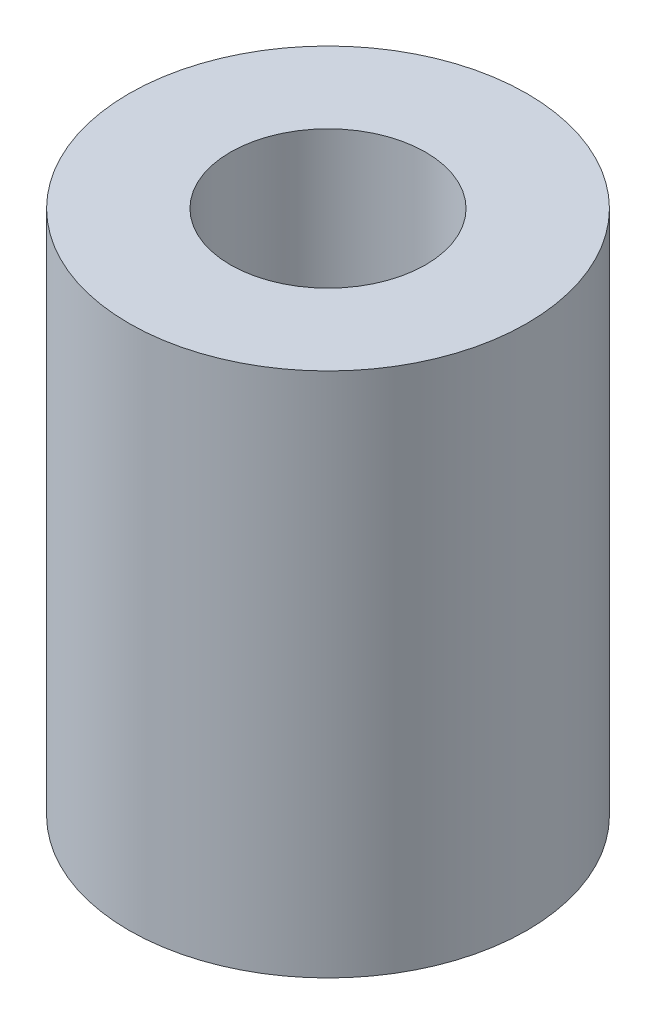
SolidWorks part; units mm, degrees
ref_plane "Front Plane" through (0, 0, 0) normal (0, 0, 1) x (1, 0, 0)
ref_plane "Top Plane" through (0, 0, 0) normal (0, 1, 0) x (1, 0, 0)
ref_plane "Right Plane" through (0, 0, 0) normal (1, 0, 0) x (0, 0, -1)
sketch "Sketch1" plane through (0, 0, 0) normal (0, 1, 0) x (1, 0, 0)
  circle A0 centre (0, 0) radius 2.65
  circle A1 centre (0, 0) radius 1.3
  dimension "D1" = 5.3
  dimension "D2" = 2.6
extrude "Boss-Extrude1" add sketch "Sketch1" along normal blind 7
